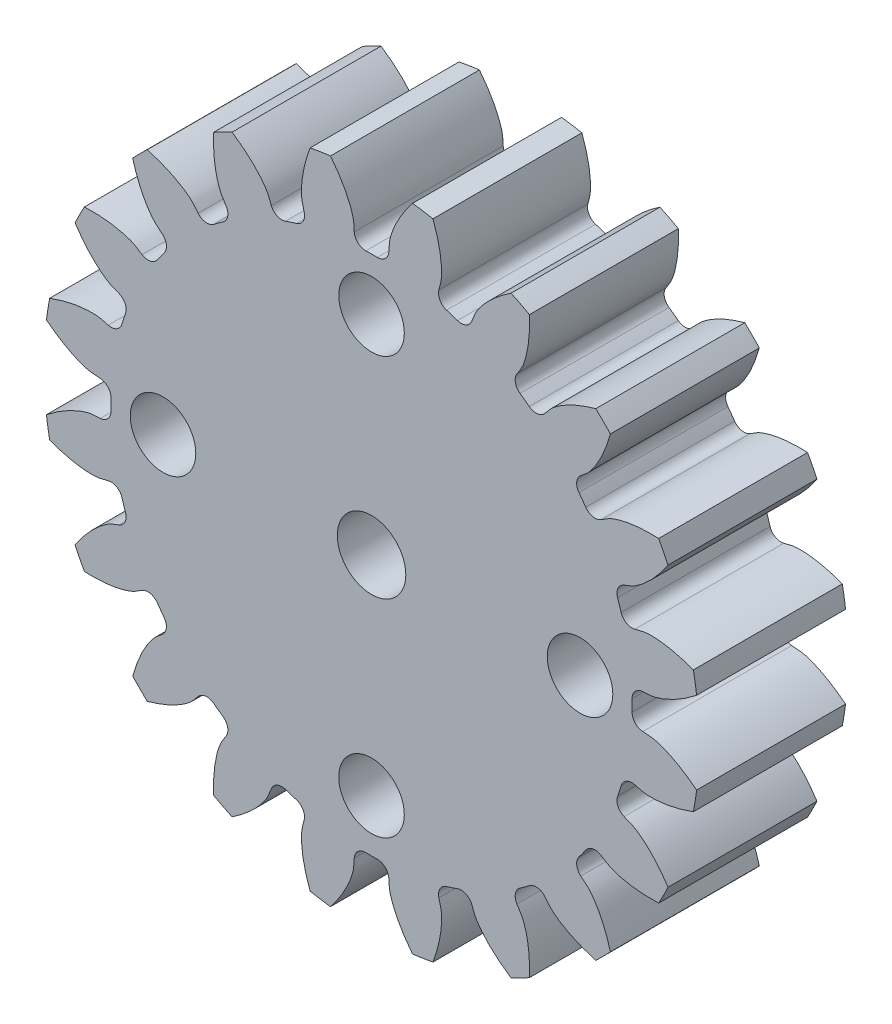
SolidWorks part; units mm, degrees
ref_plane "前视基准面" through (0, 0, 0) normal (0, 0, 1) x (1, 0, 0)
ref_plane "上视基准面" through (0, 0, 0) normal (0, 1, 0) x (1, 0, 0)
ref_plane "右视基准面" through (0, 0, 0) normal (1, 0, 0) x (0, 0, -1)
other "Configuration Table"
ref_axis "Axis1" through (0, 0, -88.99) along (0, 0, 1)
sketch "草图1" plane through (0, 0, 0) normal (0, 0, 1) x (1, 0, 0)
  circle A0 centre (0, 0) radius 11
extrude "LaShenA" add sketch "草图1" along normal blind 5
sketch "SketchA" plane through (0, 0, 5) normal (0, 0, 1) x (1, 0, 0)
  line L0 (0, 0) -> (0, 11) construction
  arc A0 (0.1927, 8.7479) -> (-0.1927, 8.7479) centre (0, 0) ccw
  arc A1 (1.7931, 11.3831) -> (-1.7931, 11.3831) centre (0, 0) ccw
  arc A2 (-0.1927, 8.7479) -> (-0.5803, 9.1044) centre (-0.201, 9.1278) cw
  arc A3 (0.5803, 9.1044) -> (0.1927, 8.7479) centre (0.201, 9.1278) cw
  circle A4 centre (0, 0) radius 9.3969 construction
  circle A5 centre (0, 0) radius 11 construction
  circle A6 centre (0, 0) radius 8.75 construction
  circle A7 centre (0, 0) radius 10 construction
  spline S0 degree 3 poles (0.5803, 9.1044) (0.586, 9.1962) (0.5881, 9.3163) (0.608, 9.4484) (0.6204, 9.5043) (0.6313, 9.5485) (0.6452, 9.5991) (0.6626, 9.656) (0.6838, 9.7191) (0.7091, 9.7882) (0.7388, 9.863) (0.7734, 9.9435) (0.813, 10.0293) (0.8581, 10.1203) (0.909, 10.2162) (0.9658, 10.3168) (1.0291, 10.4219) (1.0989, 10.531) (1.1756, 10.644) (1.2595, 10.7606) (1.3507, 10.8803) (1.4496, 11.0031) (1.5949, 11.1737) (1.7116, 11.2996) (1.7931, 11.3831) knots 0.125068 0.125068 0.125068 0.125068 0.215847 0.244833 0.257593 0.272674 0.290074 0.309794 0.331834 0.356194 0.382875 0.411875 0.443195 0.476835 0.512796 0.551076 0.591676 0.634597 0.679837 0.727398 0.777278 0.829478 0.883999 1 1 1 1
  spline S1 degree 3 poles (-0.5803, 9.1044) (-0.586, 9.1962) (-0.5881, 9.3163) (-0.608, 9.4484) (-0.6204, 9.5043) (-0.6313, 9.5485) (-0.6452, 9.5991) (-0.6626, 9.656) (-0.6838, 9.7191) (-0.7091, 9.7882) (-0.7388, 9.863) (-0.7734, 9.9435) (-0.813, 10.0293) (-0.8581, 10.1203) (-0.909, 10.2162) (-0.9658, 10.3168) (-1.0291, 10.4219) (-1.0989, 10.531) (-1.1756, 10.644) (-1.2595, 10.7606) (-1.3507, 10.8803) (-1.4496, 11.0031) (-1.5949, 11.1737) (-1.7116, 11.2996) (-1.7931, 11.3831) knots 0.125068 0.125068 0.125068 0.125068 0.215847 0.244833 0.257593 0.272674 0.290074 0.309794 0.331834 0.356194 0.382875 0.411875 0.443195 0.476835 0.512796 0.551076 0.591676 0.634597 0.679837 0.727398 0.777278 0.829478 0.883999 1 1 1 1
  dimension "D1" = 0.38
  dimension "Db" = 18.7939
  dimension "Da" = 22
  dimension "Df" = 17.5
  dimension "Dn" = 20
extrude "Cut-ExtrudeA" cut sketch "SketchA" against normal blind 30
pattern_circular "www.KYTool.cn" count 20 over 360 about axis through (0, 0, -88.99) along (0, 0, 1) of "Cut-ExtrudeA"
sketch "草图3" plane through (0, 0, 5) normal (0, 0, 1) x (1, 0, 0)
  circle A0 centre (0, 0) radius 10 construction
  dimension "D1" = 20
sketch "草图4" plane through (0, 0, 5) normal (0, 0, 1) x (1, 0, 0)
  line L0 (0, 0) -> (8.4257, 0) construction
  line L1 (0, 0) -> (0, 11.4542) construction
  circle A0 centre (7, 0) radius 1.1
  circle A2 centre (0, -7) radius 1.1
  circle A3 centre (-7, 0) radius 1.1
  circle A4 centre (0, 7) radius 1.1
  point P18 (0, 0)
  dimension "D2" = 2.2
  dimension "D1" = 7
  dimension "D3" = 4
extrude "切除-拉伸2" cut sketch "草图4" against normal through all
sketch "草图5" plane through (0, 0, 0) normal (0, 0, -1) x (-1, 0, 0)
  circle A0 centre (0, 0) radius 4
  dimension "D1" = 8
extrude "切除-拉伸3" cut sketch "草图5" against normal blind 3 contours A0
sketch "草图6" plane through (0, 0, 3) normal (0, 0, -1) x (-1, 0, 0)
  circle A0 centre (0, 0) radius 1.15
  dimension "D1" = 2.3
extrude "切除-拉伸4" cut sketch "草图6" against normal blind 3
